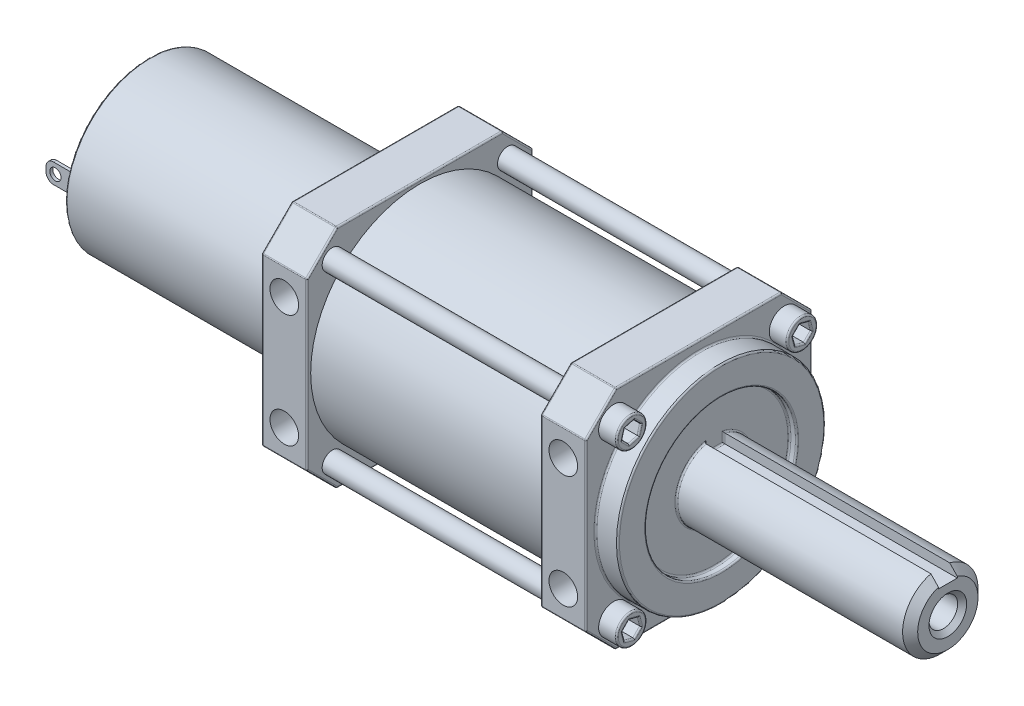
SolidWorks part; units mm, degrees
ref_plane "Front Plane" through (0, 0, 0) normal (0, 0, 1) x (1, 0, 0)
ref_plane "Top Plane" through (0, 0, 0) normal (0, 1, 0) x (1, 0, 0)
ref_plane "Right Plane" through (0, 0, 0) normal (1, 0, 0) x (0, 0, -1)
sketch "Sketch1" plane through (0, 0, 0) normal (1, 0, 0) x (0, 0, -1)
  line L1 (-19.05, 19.05) -> (19.05, 19.05)
  line L2 (-19.05, 19.05) -> (-19.05, -19.05)
  line L3 (-19.05, -19.05) -> (19.05, -19.05)
  line L4 (19.05, 19.05) -> (19.05, -19.05)
  line L5 (-19.05, 19.05) -> (19.05, -19.05) construction
  line L6 (-19.05, -19.05) -> (19.05, 19.05) construction
  point P0 (0, 0)
  dimension "D1" = 38.1
extrude "Boss-Extrude1" add sketch "Sketch1" along normal mid plane 7.62
chamfer "Chamfer1" distance 5.08 angle 45 4 edges at (0, -19.05, 19.05) (0, 19.05, 19.05) (0, 19.05, -19.05) (0, -19.05, -19.05)
sketch "Sketch2" plane through (3.81, 0, 0) normal (1, 0, 0) x (0, 0, -1)
  circle A0 centre (0, 0) radius 17.4625
  dimension "D1" = 34.925
extrude "Boss-Extrude2" add sketch "Sketch2" along normal blind 3.81
sketch "Sketch3" plane through (7.62, 0, 0) normal (1, 0, 0) x (0, 0, -1)
  circle A0 centre (0, 0) radius 12.7
  dimension "D1" = 25.4
extrude "Cut-Extrude1" cut sketch "Sketch3" against normal blind 1.27
sketch "Sketch4" plane through (6.35, 0, 0) normal (1, 0, 0) x (0, 0, -1)
  line L0 (0, 0) -> (0, 4.5609) construction
  line L2 (1.5875, 6.1484) -> (1.5875, 4.5609)
  line L3 (1.5875, 4.5609) -> (-1.5875, 4.5609)
  line L4 (-1.5875, 4.5609) -> (-1.5875, 6.1484)
  arc A0 (-1.5875, 6.1484) -> (1.5875, 6.1484) centre (0, 0) ccw
  dimension "D1" = 12.7
  dimension "D3" = 1.5875
  dimension "D4" = 3.175
extrude "Boss-Extrude3" add sketch "Sketch4" along normal blind 39.37
sketch "Sketch5" plane through (45.72, 0, 0) normal (1, 0, 0) x (0, 0, -1)
  circle A0 centre (0, 0) radius 2.413
  dimension "D1" = 4.826
extrude "Cut-Extrude2" cut sketch "Sketch5" against normal blind 12.7
sketch "Sketch6" plane through (-3.81, 0, 0) normal (-1, 0, 0) x (0, 0, 1)
  circle A0 centre (0, 0) radius 18.415
  dimension "D1" = 36.83
extrude "Boss-Extrude4" add sketch "Sketch6" along normal blind 39.37
sketch "Sketch7" plane through (-43.18, 0, 0) normal (-1, 0, 0) x (0, 0, 1)
  line L1 (-19.05, -19.05) -> (19.05, -19.05)
  line L2 (-19.05, -19.05) -> (-19.05, 19.05)
  line L3 (-19.05, 19.05) -> (19.05, 19.05)
  line L4 (19.05, -19.05) -> (19.05, 19.05)
  line L5 (-19.05, -19.05) -> (19.05, 19.05) construction
  line L6 (-19.05, 19.05) -> (19.05, -19.05) construction
  point P0 (0, 0)
  dimension "D1" = 38.1
extrude "Boss-Extrude5" add sketch "Sketch7" along normal blind 7.62
chamfer "Chamfer2" distance 5.08 angle 45 4 edges at (-46.99, -19.05, 19.05) (-46.99, -19.05, -19.05) (-46.99, 19.05, 19.05) (-46.99, 19.05, -19.05)
sketch "Sketch8" plane through (-3.81, 0, 0) normal (-1, 0, 0) x (0, 0, 1)
  line L0 (-16.51, 16.51) -> (-13.0214, 13.0214) construction
  line L1 (-13.97, 19.05) -> (-19.05, 13.97) construction
  line L2 (-13.97, 19.05) -> (-19.05, 13.97) construction
  circle A0 centre (0, 0) radius 18.415 construction
  circle A1 centre (-14.7657, 14.7657) radius 1.7145
  circle A2 centre (14.7657, 14.7657) radius 1.7145
  circle A3 centre (14.7657, -14.7657) radius 1.7145
  circle A4 centre (-14.7657, -14.7657) radius 1.7145
  dimension "D1" = 3.429
  dimension "D2" = 4
extrude "Boss-Extrude6" add sketch "Sketch8" along normal up to surface (39.37 mm away) up to face at (-43.18, 0, 0)
sketch "Sketch10" plane through (3.81, 0, 0) normal (1, 0, 0) x (0, 0, -1)
  line L0 (16.51, 16.51) -> (0, 0) construction
  line L2 (12.8103, -14.7859) -> (13.9509, -15.9266)
  line L3 (15.5091, 15.5091) -> (13.9509, 15.9266)
  line L4 (13.9509, 15.9266) -> (12.8103, 14.7859)
  line L5 (12.8103, 14.7859) -> (13.2278, 13.2278)
  line L6 (13.2278, 13.2278) -> (14.7859, 12.8103)
  line L7 (14.7859, 12.8103) -> (15.9266, 13.9509)
  line L8 (15.9266, 13.9509) -> (15.5091, 15.5091)
  line L9 (13.2278, -13.2278) -> (12.8103, -14.7859)
  line L10 (14.7859, -12.8103) -> (13.2278, -13.2278)
  line L11 (15.9266, -13.9509) -> (14.7859, -12.8103)
  line L12 (15.5091, -15.5091) -> (15.9266, -13.9509)
  line L13 (13.9509, -15.9266) -> (15.5091, -15.5091)
  line L14 (-14.7859, -12.8103) -> (-15.9266, -13.9509)
  line L15 (-13.2278, -13.2278) -> (-14.7859, -12.8103)
  line L16 (-12.8103, -14.7859) -> (-13.2278, -13.2278)
  line L17 (-13.9509, -15.9266) -> (-12.8103, -14.7859)
  line L18 (-15.5091, -15.5091) -> (-13.9509, -15.9266)
  line L19 (-15.9266, -13.9509) -> (-15.5091, -15.5091)
  line L20 (-12.8103, 14.7859) -> (-13.9509, 15.9266)
  line L21 (-13.2278, 13.2278) -> (-12.8103, 14.7859)
  line L22 (-14.7859, 12.8103) -> (-13.2278, 13.2278)
  line L23 (-15.9266, 13.9509) -> (-14.7859, 12.8103)
  line L24 (-15.5091, 15.5091) -> (-15.9266, 13.9509)
  line L25 (-13.9509, 15.9266) -> (-15.5091, 15.5091)
  line L26 (19.05, 13.97) -> (13.97, 19.05) construction
  circle A1 centre (14.3684, 14.3684) radius 2.54
  circle A2 centre (14.3684, 14.3684) radius 1.397 construction
  circle A3 centre (14.3684, -14.3684) radius 1.397 construction
  circle A4 centre (14.3684, -14.3684) radius 2.54
  circle A5 centre (-14.3684, -14.3684) radius 1.397 construction
  circle A6 centre (-14.3684, -14.3684) radius 2.54
  circle A7 centre (-14.3684, 14.3684) radius 1.397 construction
  circle A8 centre (-14.3684, 14.3684) radius 2.54
  dimension "D1" = 5.08
  dimension "D2" = 2.794
  dimension "D4" = 20.32
  dimension "D3" = 4
extrude "Boss-Extrude9" add sketch "Sketch10" along normal blind 3.048
sketch "Sketch11" plane through (-50.8, 0, 0) normal (-1, 0, 0) x (0, 0, 1)
  circle A0 centre (0, 0) radius 13.97
  dimension "D1" = 27.94
extrude "Boss-Extrude10" add sketch "Sketch11" along normal blind 38.1
sketch "Sketch12" plane through (-88.9, 0, 0) normal (-1, 0, 0) x (0, 0, 1)
  circle A0 centre (0, 0) radius 5.08
  dimension "D1" = 10.16
extrude "Boss-Extrude11" add sketch "Sketch12" along normal blind 3.048
fillet "Fillet2" radius 1.27 1 edges at (-91.948, 0, 5.08)
sketch "Sketch14" plane through (-88.9, 0, 0) normal (-1, 0, 0) x (0, 0, 1)
  line L0 (13.97, 0) -> (-13.97, 0) construction
  line L1 (0, 0) -> (0, 3.81) construction
  line L2 (10.414, 1.651) -> (10.922, 1.651)
  line L3 (10.414, 1.651) -> (10.414, -1.651)
  line L4 (10.414, -1.651) -> (10.922, -1.651)
  line L5 (10.922, 1.651) -> (10.922, -1.651)
  line L6 (10.414, 1.651) -> (10.922, -1.651) construction
  line L7 (10.414, -1.651) -> (10.922, 1.651) construction
  line L8 (-10.414, 1.651) -> (-10.922, 1.651)
  line L9 (-10.414, -1.651) -> (-10.922, -1.651)
  line L10 (-10.922, 1.651) -> (-10.922, -1.651)
  line L11 (-10.414, 1.651) -> (-10.414, -1.651)
  circle A0 centre (0, 0) radius 13.97 construction
  circle A1 centre (0, 0) radius 13.97 construction
  circle A2 centre (0, 0) radius 3.81 construction
  point P7 (10.668, 0)
  dimension "D1" = 3.048
  dimension "D2" = 3.302
  dimension "D3" = 0.508
extrude "Boss-Extrude12" add sketch "Sketch14" along normal blind 6.35
sketch "Sketch15" plane through (0, 0, -10.922) normal (0, 0, -1) x (-1, 0, 0)
  line L0 (92.075, 1.651) -> (92.075, -1.651) construction
  line L1 (95.25, 1.651) -> (88.9, 1.651) construction
  line L2 (95.25, -1.651) -> (88.9, -1.651) construction
  line L3 (92.075, 0) -> (95.25, 0) construction
  line L4 (95.25, 1.651) -> (95.25, -1.651) construction
  circle A0 centre (93.6625, 0) radius 0.9525
  dimension "D1" = 1.905
extrude "Cut-Extrude3" cut sketch "Sketch15" against normal through all
fillet "Fillet12" radius 0.254 94 edges at (-88.9, 0, -10.922) (-88.9, -1.651, -10.668) (-88.9, 0, -10.414) (-88.9, 1.651, -10.668) (-88.9, 0, 5.08) (-88.9, 0, 13.97) (-88.9, 0, 10.414) (-88.9, -1.651, 10.668) (-88.9, 0, 10.922) (-88.9, 1.651, 10.668) (-43.18, 0, 19.05) (-50.8, 0, 19.05) (-43.18, 16.51, 16.51) (-46.99, 13.97, 19.05) (-50.8, 16.51, 16.51) (3.81, 19.05, 0) (-3.81, 19.05, 0) (-43.18, 19.05, 0) (-46.99, 19.05, 13.97) (-50.8, 19.05, 0) (-43.18, 16.51, -16.51) (-46.99, 19.05, -13.97) (-50.8, 16.51, -16.51) (0, 19.05, -13.97) (-3.81, 16.51, -16.51) (3.81, 16.51, -16.51) (3.81, 0, -19.05) (0, 13.97, -19.05) (-3.81, 0, -19.05) (0, -13.97, -19.05) (-3.81, -16.51, -16.51) (3.81, -16.51, -16.51) (-46.99, 13.97, -19.05) (-50.8, 0, -19.05) (-43.18, 0, -19.05) (-43.18, -16.51, -16.51) (-46.99, -13.97, -19.05) (-50.8, -16.51, -16.51) (-46.99, -13.97, 19.05) (-43.18, -16.51, 16.51) (-50.8, -16.51, 16.51) (-46.99, -19.05, -13.97) (-50.8, -19.05, 0) (-46.99, -19.05, 13.97) (-43.18, -19.05, 0) (0, -19.05, -13.97) (-3.81, -19.05, 0) (3.81, -19.05, 0) (0, -19.05, 13.97) (-3.81, -16.51, 16.51) (3.81, -16.51, 16.51) (-3.81, 16.51, 16.51) (0, 19.05, 13.97) (3.81, 16.51, 16.51) (0, 13.97, 19.05) (3.81, 0, 19.05) (0, -13.97, 19.05) (-3.81, 0, 19.05) (6.35, -6.35, 0) (6.35, 5.3546, -1.5875) (6.35, 4.5609, 0) (6.35, 5.3546, 1.5875) (6.35, 0, -12.7) (3.81, 0, -17.4625) (7.62, 0, -17.4625) (7.62, 0, -12.7) (6.858, 13.3806, 15.3562) (6.858, 13.019, 14.0068) (6.858, 14.0068, 13.019) (6.858, 15.3562, 13.3806) (6.858, 15.7178, 14.73) (6.858, 14.73, 15.7178) (6.858, 14.3684, 11.8284) (6.858, 15.3562, -13.3806) (6.858, 14.0068, -13.019) (6.858, 13.019, -14.0068) (6.858, 13.3806, -15.3562) (6.858, 14.73, -15.7178) (6.858, 15.7178, -14.73) (6.858, 14.3684, -16.9084) (6.858, -13.3806, -15.3562) (6.858, -13.019, -14.0068) (6.858, -14.0068, -13.019) (6.858, -15.3562, -13.3806) (6.858, -15.7178, -14.73) (6.858, -14.73, -15.7178) (6.858, -14.3684, -16.9084) (6.858, -15.3562, 13.3806) (6.858, -14.0068, 13.019) (6.858, -13.019, 14.0068) (6.858, -13.3806, 15.3562) (6.858, -14.73, 15.7178) (6.858, -15.7178, 14.73) (6.858, -14.3684, 11.8284)
fillet "Fillet13" radius 1.27 4 edges at (-95.25, -1.651, -10.668) (-95.25, 1.651, -10.668) (-95.25, 1.651, 10.668) (-95.25, -1.651, 10.668)
chamfer "Chamfer3" distance 0.762 angle 45 1 edges at (45.72, 0, -2.413)
chamfer "Chamfer4" distance 1.27 angle 45 1 edges at (45.72, -6.35, 0)
sketch "Sketch16" plane through (0, 0, -19.05) normal (0, 0, -1) x (-1, 0, 0)
  line L0 (46.99, -13.8648) -> (46.99, 13.8648) construction
  line L1 (50.546, 0) -> (43.434, 0) construction
  line L2 (0, 13.8648) -> (0, -13.8648) construction
  line L3 (3.556, 13.8648) -> (-3.556, 13.8648) construction
  line L4 (50.546, -13.8648) -> (50.546, 13.8648)
  line L5 (50.546, 13.8648) -> (43.434, 13.8648)
  line L6 (43.434, 13.8648) -> (43.434, -13.8648)
  line L7 (43.434, -13.8648) -> (50.546, -13.8648)
  line L8 (50.546, -13.8648) -> (50.546, 13.8648) construction
  line L9 (50.546, 13.8648) -> (43.434, 13.8648) construction
  line L10 (43.434, 13.8648) -> (43.434, -13.8648) construction
  line L11 (43.434, -13.8648) -> (50.546, -13.8648) construction
  line L12 (-3.556, -13.8648) -> (3.556, -13.8648) construction
  line L13 (0, 13.8648) -> (46.99, 13.8648) construction
  line L14 (23.495, 13.8648) -> (23.495, -13.8648) construction
  line L15 (46.99, -13.8648) -> (0, -13.8648) construction
  circle A0 centre (46.99, -9.525) radius 2.413
  circle A1 centre (46.99, 9.525) radius 2.413
  circle A2 centre (0, -9.525) radius 2.413
  circle A3 centre (0, 9.525) radius 2.413
  dimension "D2" = 4.826
  dimension "D3" = 9.525
  dimension "D1" = 0
extrude "Cut-Extrude4" cut sketch "Sketch16" against normal blind 10.16
mirror "Mirror1" about plane through (0, 0, 0) normal (0, 0, 1) of "Cut-Extrude4"
